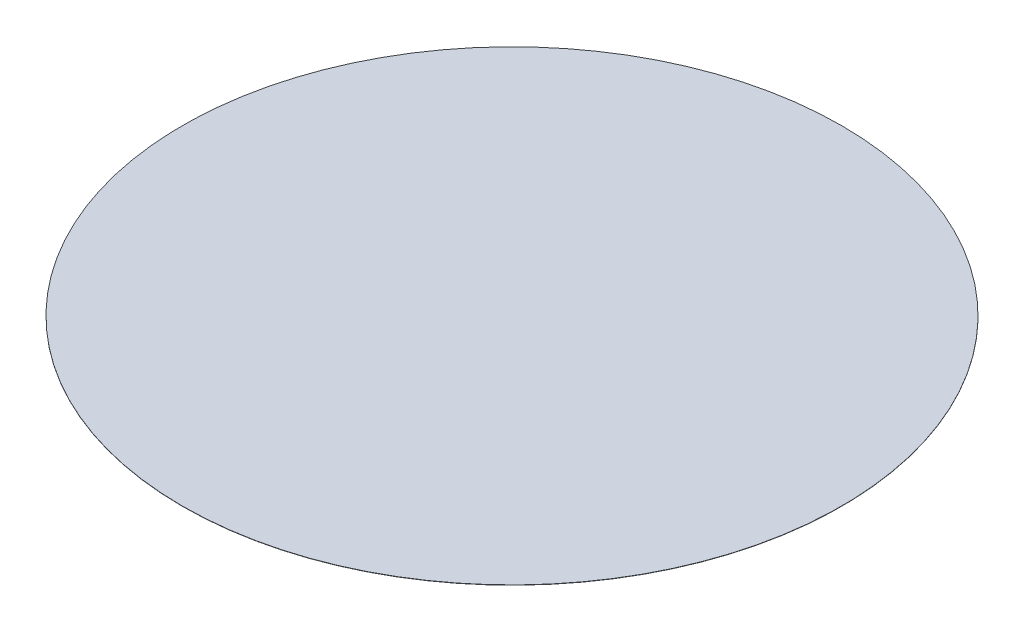
SolidWorks part; units mm, degrees
ref_plane "Front Plane" through (0, 0, 0) normal (0, 0, 1) x (1, 0, 0)
ref_plane "Top Plane" through (0, 0, 0) normal (0, 1, 0) x (1, 0, 0)
ref_plane "Right Plane" through (0, 0, 0) normal (1, 0, 0) x (0, 0, -1)
sketch "Sketch1" plane through (0, 0, 0) normal (0, 1, 0) x (1, 0, 0)
  circle A0 centre (0, 0) radius 2500
  dimension "D1" = 5000
extrude "Boss-Extrude1" add sketch "Sketch1" along normal mid plane 2
equation "\"radius\"= 5m"
equation "\"D1@Sketch1\"=\"radius\""
equation "\"yaa\"= ( 5mm )"
equation "\"ya\"= ( 2 * 4 ) * ( 5mm )"
equation "\"ye\"= 5mm * 2"
equation "\"yo\"= ( ( 0 ) )"
equation "\"yu\"= 3m + 3mm"
